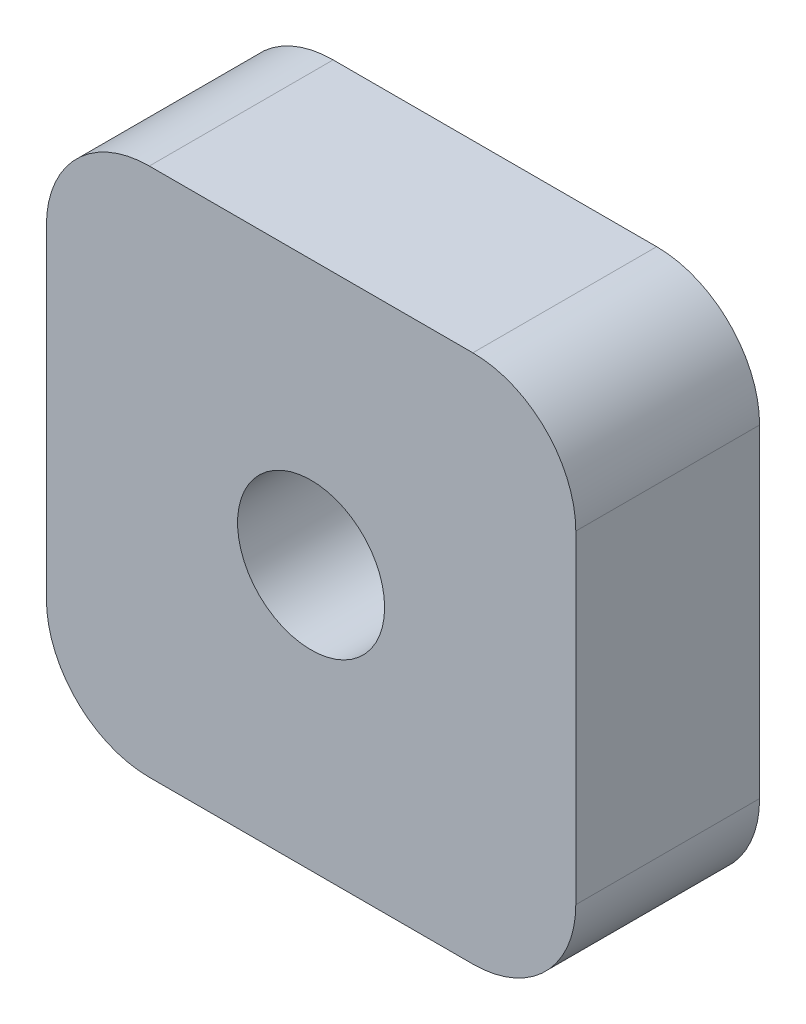
SolidWorks part; units mm, degrees
material "ASTM A36 Aço"
ref_plane "Plano frontal" through (0, 0, 0) normal (0, 0, 1) x (1, 0, 0)
ref_plane "Plano superior" through (0, 0, 0) normal (0, 1, 0) x (1, 0, 0)
ref_plane "Plano direito" through (0, 0, 0) normal (1, 0, 0) x (0, 0, -1)
sketch "Esboço1" plane through (0, 0, 0) normal (0, 0, 1) x (1, 0, 0)
  line L1 (-11, 18) -> (11, 18)
  line L2 (-18, 11) -> (-18, -11)
  line L3 (-11, -18) -> (11, -18)
  line L4 (18, 11) -> (18, -11)
  line L5 (-18, 18) -> (18, -18) construction
  line L6 (-18, -18) -> (18, 18) construction
  circle A1 centre (0, 0) radius 5
  arc A2 (-18, -11) -> (-11, -18) centre (-11, -11) ccw
  arc A3 (11, -18) -> (18, -11) centre (11, -11) ccw
  arc A4 (18, 11) -> (11, 18) centre (11, 11) ccw
  arc A5 (-11, 18) -> (-18, 11) centre (-11, 11) ccw
  point P0 (0, 0)
  dimension "D2" = 10
  dimension "D4" = 7
  dimension "D1" = 36
extrude "Ressalto-extrusão1" add sketch "Esboço1" along normal blind 12.5
hole_wizard "Furo roscado de M41" positions "Esboço4" profile "Esboço5" tap size "M4" standard "ISO"
sketch "Esboço4" plane through (0, 0, 0) normal (0, 0, -1) x (-1, 0, 0)
  line L0 (18, 11) -> (18, -11) construction
  line L1 (11, -18) -> (-11, -18) construction
  line L3 (-18, 0) -> (18, 0) construction
  line L6 (0, 18) -> (0, -18) construction
  point P0 (11, -11)
  point P59 (0, 0)
  point P95 (0, 0)
  point P125 (0, 0)
  point P192 (0, 0)
  point P195 (11, 11)
  point P196 (-11, -11)
  point P197 (-11, 11)
  dimension "D1" = 7
  dimension "D2" = 7
sketch "Esboço5" plane through (-11, -11, 0) normal (1, 0, 0) x (0, 1, 0)
  line L0 (0, 0) -> (0, 7.9914)
  line L1 (0, 7.9914) -> (1.65, 7)
  line L2 (1.65, 7) -> (1.65, 4)
  line L3 (1.65, 4) -> (2, 4)
  line L4 (2, 4) -> (2, 0)
  line L5 (2, 0) -> (0, 0)
  line L10 (0, 7.9914) -> (-1.65, 7) construction
  line L11 (0, -6.35) -> (0, 107.95) construction
  dimension "Tap Drill Dia." = 3.3
  dimension "Tap Drill Depth" = 7
  dimension "Thread Major Dia." = 4
  dimension "Thread Depth" = 4
  dimension "Drill Angle" = 118
